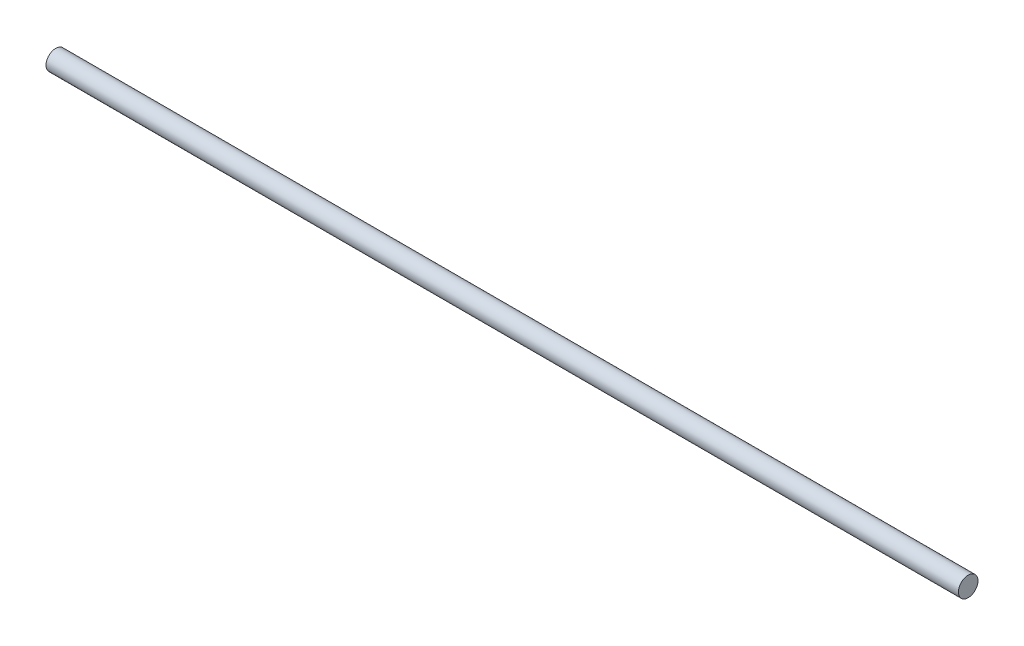
SolidWorks part; units mm, degrees
ref_plane "Front Plane" through (0, 0, 0) normal (0, 0, 1) x (1, 0, 0)
ref_plane "Top Plane" through (0, 0, 0) normal (0, 1, 0) x (1, 0, 0)
ref_plane "Right Plane" through (0, 0, 0) normal (1, 0, 0) x (0, 0, -1)
sketch "Sketch1" plane through (0, 0, 0) normal (1, 0, 0) x (0, 0, -1)
  circle A0 centre (0, 0) radius 4
  dimension "D1" = 8
extrude "Boss-Extrude1" add sketch "Sketch1" along normal blind 373
